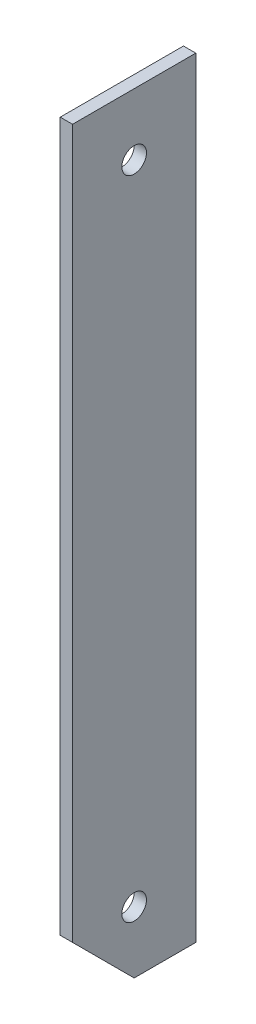
SolidWorks part; units mm, degrees
ref_plane "Front Plane" through (0, 0, 0) normal (0, 0, 1) x (1, 0, 0)
ref_plane "Top Plane" through (0, 0, 0) normal (0, 1, 0) x (1, 0, 0)
ref_plane "Right Plane" through (0, 0, 0) normal (1, 0, 0) x (0, 0, -1)
sketch "Sketch1" plane through (0, 0, 0) normal (1, 0, 0) x (0, 0, -1)
  line L0 (0, 125) -> (0, -125) construction
  line L1 (-20, 125) -> (20, 125)
  line L2 (-20, 125) -> (-20, -125)
  line L3 (-20, -125) -> (20, -125)
  line L4 (20, 125) -> (20, -125)
  line L5 (-20, 125) -> (20, -125) construction
  line L6 (-20, -125) -> (20, 125) construction
  line L7 (0, 0) -> (45.6121, 0) construction
  circle A0 centre (0, 105) radius 4
  circle A1 centre (0, -105) radius 4
  point P0 (0, 0)
  dimension "D3" = 20
  dimension "D1" = 125
  dimension "D2" = 40
  dimension "D4" = 125
  dimension "D6" = 20
  dimension "D7" = 20
  dimension "D8" = 20
extrude "Boss-Extrude1" add sketch "Sketch1" along normal blind 4
chamfer "Chamfer3" distance 20 angle 45 1 edges at (2, -125, 20)
